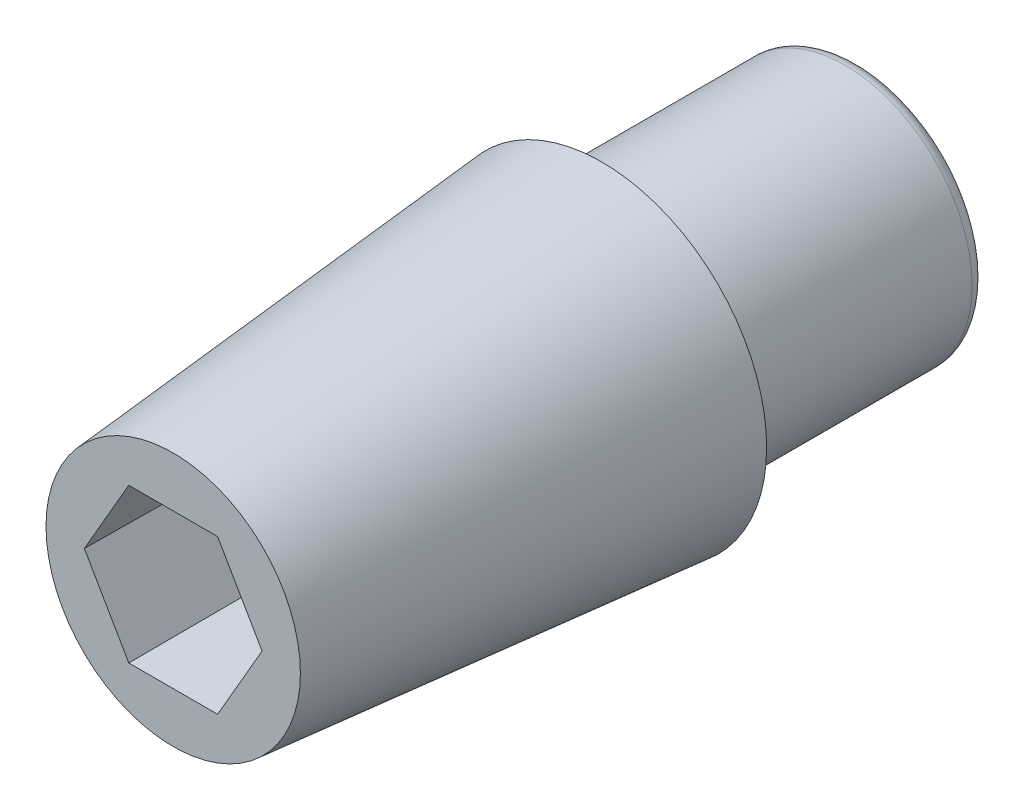
SolidWorks part; units mm, degrees
ref_plane "Front Plane" through (0, 0, 0) normal (0, 0, 1) x (1, 0, 0)
ref_plane "Top Plane" through (0, 0, 0) normal (0, 1, 0) x (1, 0, 0)
ref_plane "Right Plane" through (0, 0, 0) normal (1, 0, 0) x (0, 0, -1)
sketch "Sketch1" plane through (0, 0, 0) normal (0, 1, 0) x (1, 0, 0)
  line L0 (5.7623, 0) -> (0, 0)
  line L1 (0, 0) -> (0, -15)
  line L2 (0, -15) -> (4.45, -15)
  line L3 (4.45, -15) -> (5.7623, 0)
  line L4 (0, 0) -> (0, -15) construction
revolve "Revolve1" add sketch "Sketch1" angle 360 about L4
sketch "Sketch2" plane through (0, 0, 0) normal (0, 0, -1) x (-1, 0, 0)
  circle A0 centre (0, 0) radius 4.45
extrude "Boss-Extrude1" add sketch "Sketch2" along normal blind 9
sketch "Sketch3" plane through (0, 0, 15) normal (0, 0, 1) x (1, 0, 0)
  line L0 (1.5542, 2.692) -> (-1.5542, 2.692)
  line L1 (-1.5542, 2.692) -> (-3.1084, 0)
  line L2 (-3.1084, 0) -> (-1.5542, -2.692)
  line L3 (-1.5542, -2.692) -> (1.5542, -2.692)
  line L4 (1.5542, -2.692) -> (3.1084, 0)
  line L5 (3.1084, 0) -> (1.5542, 2.692)
extrude "Cut-Extrude1" cut sketch "Sketch3" against normal blind 22 draft 0.5
sketch "Sketch4" plane through (0, 0, 0) normal (0, 1, 0) x (1, 0, 0)
  line L0 (0.5, 7) -> (0, 7)
  line L1 (0, 7) -> (0, 6.75)
  line L2 (0, 6.75) -> (0.4781, 6.75)
  line L3 (0.4781, 6.75) -> (0.5, 7)
  line L4 (0, 7) -> (0, 6.75) construction
revolve "Revolve2" add sketch "Sketch4" angle 360 about L4
fillet "Fillet1" radius 0.1 2 edges at (0.4781, 0, -6.75) (0.5, 0, -7)
fillet "Fillet2" radius 0.5 1 edges at (-4.45, 0, -9)
